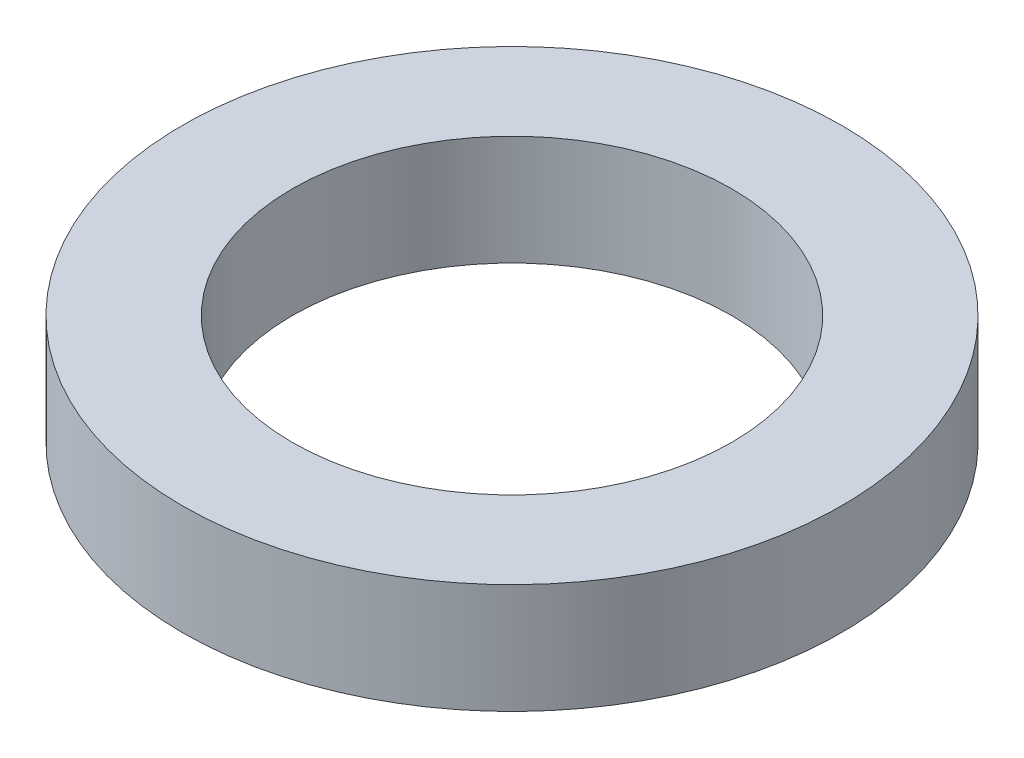
SolidWorks part; units mm, degrees
material "Cast Alloy Steel"
ref_plane "Front Plane" through (0, 0, 0) normal (0, 0, 1) x (1, 0, 0)
ref_plane "Top Plane" through (0, 0, 0) normal (0, 1, 0) x (1, 0, 0)
ref_plane "Right Plane" through (0, 0, 0) normal (1, 0, 0) x (0, 0, -1)
sketch "Sketch1" plane through (0, 0, 0) normal (0, 1, 0) x (1, 0, 0)
  circle A0 centre (0, 0) radius 1
  circle A1 centre (0, 0) radius 1.5
  dimension "D1" = 2
  dimension "D2" = 3
extrude "Boss-Extrude1" add sketch "Sketch1" along normal blind 0.5
